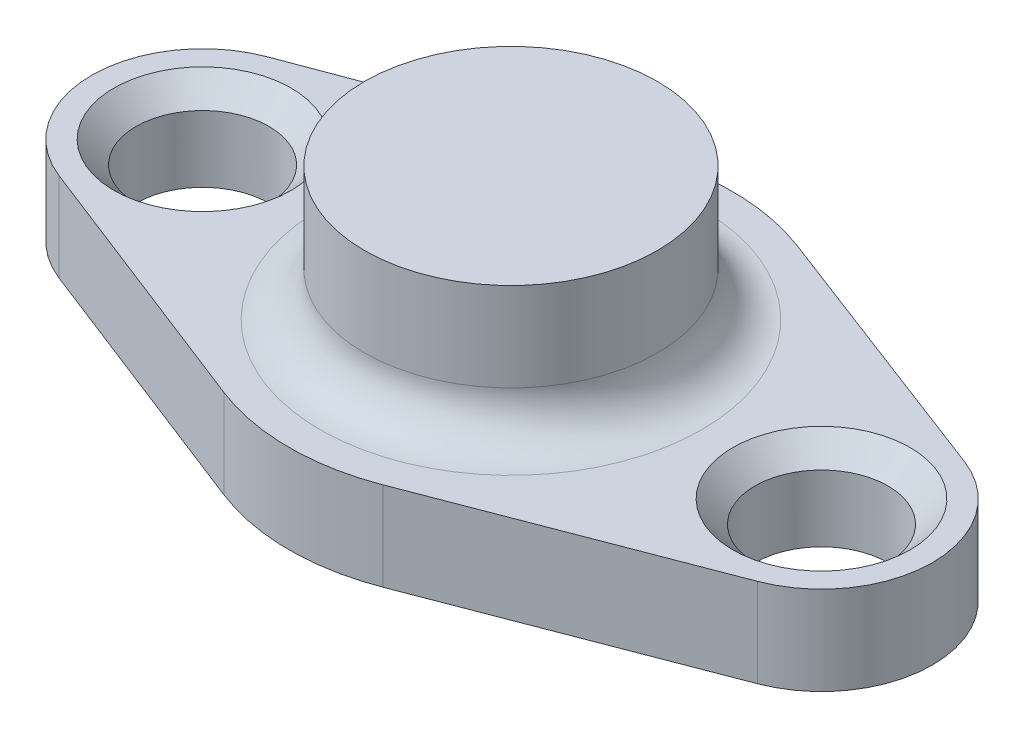
SolidWorks part; units mm, degrees
ref_plane "Plane1" through (0, 0, 0) normal (0, 0, 1) x (1, 0, 0)
ref_plane "Plane2" through (0, 0, 0) normal (0, 1, 0) x (1, 0, 0)
ref_plane "Plane3" through (0, 0, 0) normal (1, 0, 0) x (0, 0, -1)
sketch "Эскиз1" plane through (0, 0, 0) normal (0, -1, 0) x (-1, 0, 0)
  line L0 (-78.9175, 23.3886) -> (-17.835, 46.7109)
  line L1 (17.5567, 46.8163) -> (78.7769, 23.858)
  line L2 (79.077, -22.8436) -> (18.1569, -46.5868)
  line L3 (-17.8793, -46.694) -> (-78.9396, -23.3139)
  arc A0 (-17.8793, -46.694) -> (18.1569, -46.5868) centre (0, 0) ccw
  arc A1 (79.077, -22.8436) -> (78.7769, 23.858) centre (69.9986, 0.4498) ccw
  arc A2 (-78.9175, 23.3886) -> (-78.9396, -23.3139) centre (-70, 0.0331) ccw
  arc A3 (17.5567, 46.8163) -> (-17.835, 46.7109) centre (0, 0) ccw
  dimension "D1" = 100
  dimension "D2" = 50
  dimension "D3" = 50
  dimension "D4" = 70
  dimension "D5" = 70
extrude "Основание-Вытянуть" add sketch "Эскиз1" along normal blind 20
sketch "Эскиз2" plane through (0, 0, 0) normal (0, 1, 0) x (-1, 0, 0)
  circle A0 centre (0, 0) radius 33.0333
extrude "Бобышка-Вытянуть1" add sketch "Эскиз2" along normal blind 30
sketch "Эскиз3" plane through (0, 0, 0) normal (0, 1, 0) x (-1, 0, 0)
  circle A0 centre (-70, -0.0331) radius 15
  circle A1 centre (69.9986, -0.4498) radius 15
  arc A2 (78.7769, -23.858) -> (79.077, 22.8436) centre (69.9986, -0.4498) ccw construction
  arc A3 (-78.9396, 23.3139) -> (-78.9175, -23.3886) centre (-70, -0.0331) ccw construction
  dimension "D1" = 30
  dimension "D2" = 30
extrude "Вырез-Вытянуть1" cut sketch "Эскиз3" against normal through all
sketch "Эскиз4" plane through (0, 30, 0) normal (0, 1, 0) x (-1, 0, 0)
  circle A0 centre (0, 0) radius 22.7816
extrude "Вырез-Вытянуть2" [suppressed] cut sketch "Эскиз4" against normal through all
fillet "Скругление1" radius 10 1 edges at (33.0333, 0, 0)
chamfer "Фаска1" distance 5 angle 45 2 edges at (55, 0, -0.0331) (-84.9986, 0, -0.4498)
